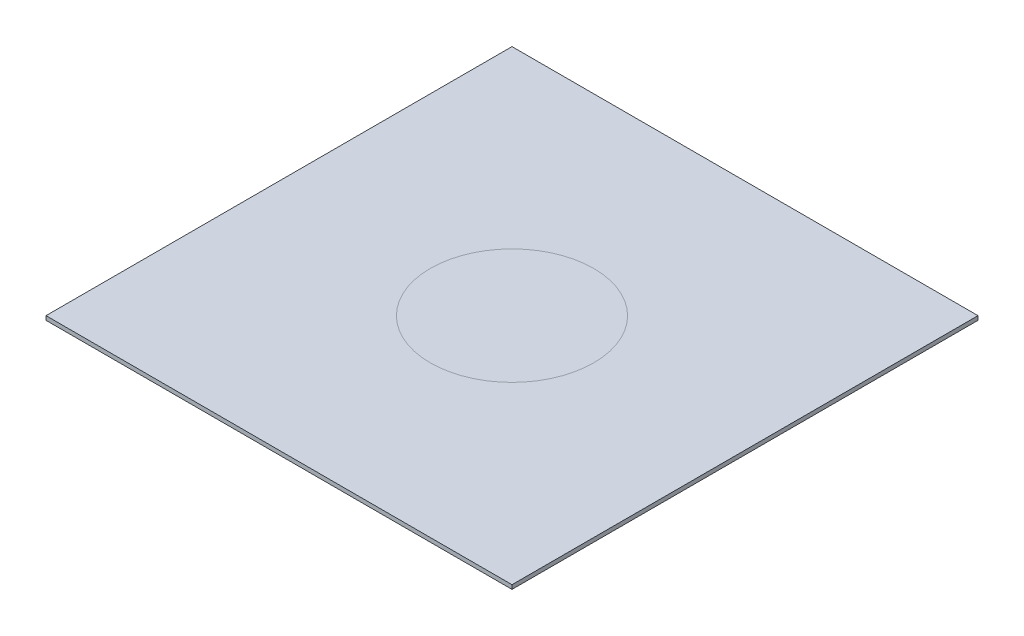
SolidWorks part; units mm, degrees
material "Zirconia"
ref_plane "Front Plane" through (0, 0, 0) normal (0, 0, 1) x (1, 0, 0)
ref_plane "Top Plane" through (0, 0, 0) normal (0, 1, 0) x (1, 0, 0)
ref_plane "Right Plane" through (0, 0, 0) normal (1, 0, 0) x (0, 0, -1)
sketch "Sketch1" plane through (0, 0, 0) normal (0, 1, 0) x (1, 0, 0)
  line L1 (-57, -57) -> (57, -57)
  line L2 (-57, -57) -> (-57, 57)
  line L3 (-57, 57) -> (57, 57)
  line L4 (57, -57) -> (57, 57)
  line L5 (-57, -57) -> (57, 57) construction
  line L6 (-57, 57) -> (57, -57) construction
  point P0 (0, 0)
  dimension "D1" = 114
extrude "Boss-Extrude1" add sketch "Sketch1" along normal mid plane 1
sketch "Sketch2" plane through (0, 0.5, 0) normal (0, 1, 0) x (1, 0, 0)
  circle A0 centre (0, 0) radius 20
  dimension "D1" = 40
split line "Split Line1"
equation "\"panel_width\"= 114mm"
equation "\"finger_joint_width\" = 25mm"
equation "\"D1@Sketch1\"=\"panel_width\""
